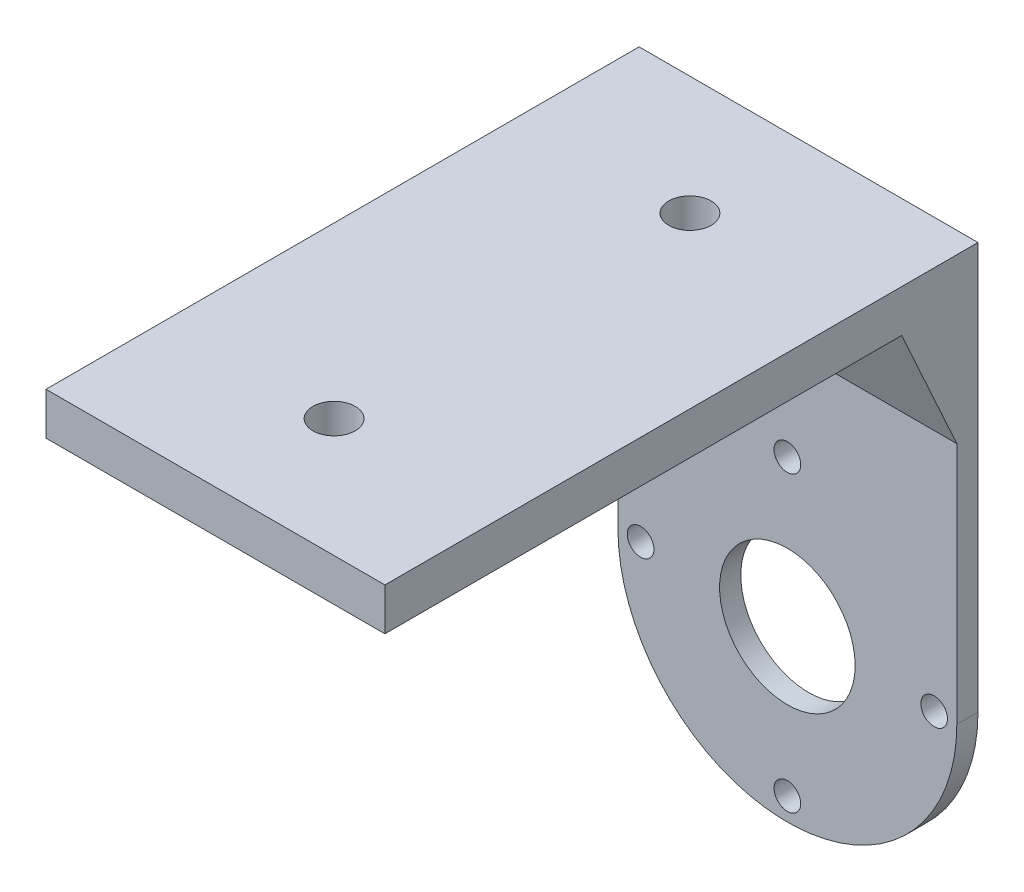
SolidWorks part; units mm, degrees
ref_plane "Front Plane" through (0, 0, 0) normal (0, 0, 1) x (1, 0, 0)
ref_plane "Top Plane" through (0, 0, 0) normal (0, 1, 0) x (1, 0, 0)
ref_plane "Right Plane" through (0, 0, 0) normal (1, 0, 0) x (0, 0, -1)
sketch "Sketch1" plane through (0, 0, 0) normal (0, 0, 1) x (1, 0, 0)
  line L6 (-25.4, 0) -> (-25.4, 60.96)
  line L7 (-25.4, 60.96) -> (25.4, 60.96)
  line L8 (25.4, 0) -> (25.4, 60.96)
  circle A1 centre (0, 0) radius 10.16
  circle A4 centre (0, -22) radius 2
  circle A7 centre (-22, 0) radius 2
  circle A9 centre (0, 22) radius 2
  circle A11 centre (22, 0) radius 2
  arc A12 (-25.4, 0) -> (25.4, 0) centre (0, 0) ccw
  point P23 (0, 0)
  dimension "D1" = 50.8
  dimension "D2" = 20.32
  dimension "D7" = 4
  dimension "D5" = 60.96
  dimension "D3" = 4
  dimension "D4" = 22
  dimension "D6" = 50.8
extrude "Boss-Extrude1" add sketch "Sketch1" along normal blind 3.175
sketch "Sketch2" plane through (0, 60.96, 0) normal (0, 1, 0) x (1, 0, 0)
  line L1 (-25.4, 0) -> (25.4, 0)
  line L2 (-25.4, 0) -> (-25.4, -88.9)
  line L3 (-25.4, -88.9) -> (25.4, -88.9)
  line L4 (25.4, 0) -> (25.4, -88.9)
  circle A0 centre (0, -17.78) radius 3.175
  circle A1 centre (0, -71.12) radius 3.175
  dimension "D6" = 6.35
  dimension "D7" = 6.35
  dimension "D1" = 50.8
  dimension "D2" = 25.4
  dimension "D3" = 17.78
  dimension "D4" = 71.12
  dimension "D5" = 88.9
extrude "Boss-Extrude2" add sketch "Sketch2" against normal blind 6.35
sketch "Sketch3" plane through (-25.4, 0, 0) normal (-1, 0, 0) x (0, 0, 1)
  line L0 (11.4416, 54.61) -> (3.175, 36.4396)
  line L1 (3.175, 54.61) -> (88.9, 54.61) construction
  line L2 (3.175, 54.61) -> (3.175, 0) construction
  line L3 (3.175, 36.4396) -> (3.175, 54.61)
  line L4 (3.175, 54.61) -> (11.4416, 54.61)
  point P8 (11.4416, 54.61)
  point P9 (3.175, 36.4396)
extrude "Boss-Extrude3" add sketch "Sketch3" against normal up to surface (50.8 mm away) up to face at (25.4, 38.5233, 30.6917)
